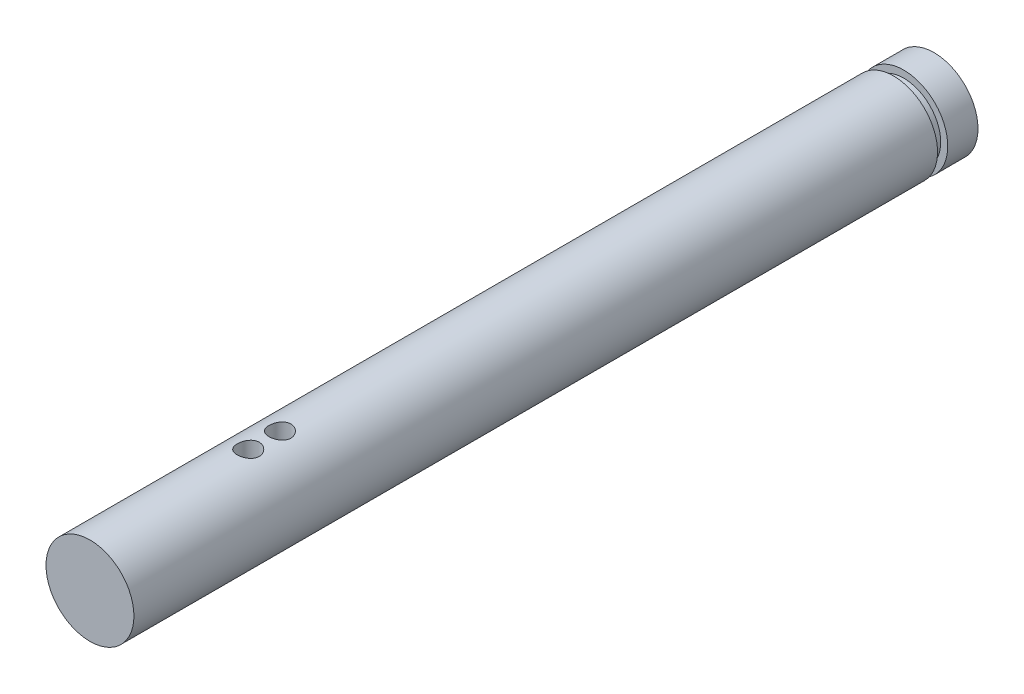
SolidWorks part; units mm, degrees
material "6061 Alloy"
ref_plane "Front Plane" through (0, 0, 0) normal (0, 0, 1) x (1, 0, 0)
ref_plane "Top Plane" through (0, 0, 0) normal (0, 1, 0) x (1, 0, 0)
ref_plane "Right Plane" through (0, 0, 0) normal (1, 0, 0) x (0, 0, -1)
sketch "Sketch1" plane through (0, 0, 0) normal (0, 0, 1) x (1, 0, 0)
  circle A0 centre (0, 0) radius 3.175
  dimension "D1" = 6.35
extrude "Boss-Extrude1" add sketch "Sketch1" along normal blind 35.56
sketch "Sketch3" plane through (0, 0, 0) normal (0, 1, 0) x (1, 0, 0)
  line L0 (0, 0) -> (0, -35.56) construction
  line L1 (-3.175, -35.56) -> (3.175, -35.56) construction
  line L2 (3.175, -35.56) -> (3.175, 0) construction
  line L3 (3.175, -2.1844) -> (2.667, -2.1844)
  line L4 (3.175, -2.1844) -> (3.175, -2.921)
  line L5 (3.175, -2.921) -> (2.667, -2.921)
  line L6 (2.667, -2.1844) -> (2.667, -2.921)
  line L8 (-5.3479, 0) -> (5.3479, 0) construction
  dimension "D1" = 0.7366
  dimension "D2" = 0.508
  dimension "D3" = 2.921
revolve "Cut-Revolve3" cut sketch "Sketch3" angle 360 about L0
sketch "Sketch5" plane through (0, 0, 35.56) normal (0, 0, 1) x (1, 0, 0)
  circle A0 centre (0, 0) radius 3.175
  circle A1 centre (0, 0) radius 3.175 construction
extrude "Boss-Extrude2" add sketch "Sketch5" along normal blind 25.4
sketch "Sketch4" plane through (0, 0, 0) normal (0, 1, 0) x (1, 0, 0)
  line L0 (-3.175, -60.96) -> (3.175, -60.96) construction
  line L1 (-5.3479, 0) -> (5.3479, 0) construction
  circle A0 centre (0, -47.244) radius 0.7937
  circle A1 centre (0, -49.53) radius 0.7937
  dimension "D1" = 1.5875
  dimension "D3" = 1.5875
  dimension "D2" = 47.244
  dimension "D4" = 11.43
extrude "Cut-Extrude1" cut sketch "Sketch4" against normal through all both and the other way through all
